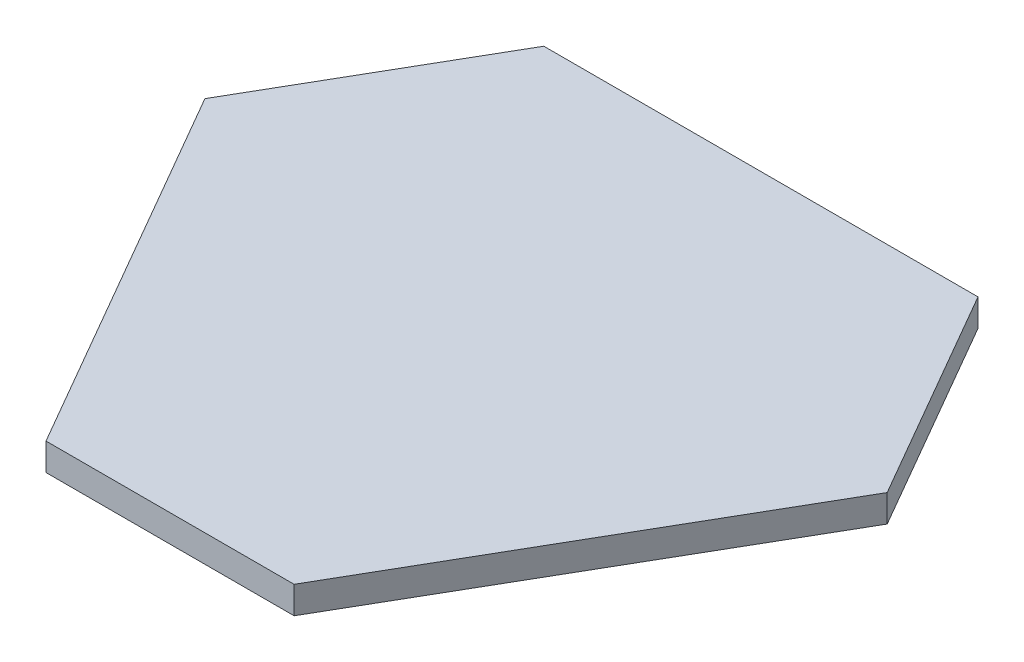
SolidWorks part; units mm, degrees
ref_plane "Front Plane" through (0, 0, 0) normal (0, 0, 1) x (1, 0, 0)
ref_plane "Top Plane" through (0, 0, 0) normal (0, 1, 0) x (1, 0, 0)
ref_plane "Right Plane" through (0, 0, 0) normal (1, 0, 0) x (0, 0, -1)
sketch "Sketch1" plane through (0, 0, 0) normal (0, 1, 0) x (1, 0, 0)
  line L0 (0, 150) -> (-129.9038, -75)
  line L1 (-129.9038, -75) -> (129.9038, -75)
  line L2 (129.9038, -75) -> (0, 150)
  line L3 (0, -125) -> (-108.2532, 62.5)
  line L4 (-108.2532, 62.5) -> (108.2532, 62.5)
  line L5 (108.2532, 62.5) -> (0, -125)
  circle A0 centre (0, 0) radius 150 construction
  circle A1 centre (0, 0) radius 75 construction
  circle A2 centre (0, 0) radius 125 construction
  circle A3 centre (0, 0) radius 62.5 construction
  dimension "D1" = 300
  dimension "D2" = 250
extrude "Boss-Extrude1" add sketch "Sketch1" along normal blind 6.35 contours L5 L2 L4 L0 L3 L1
